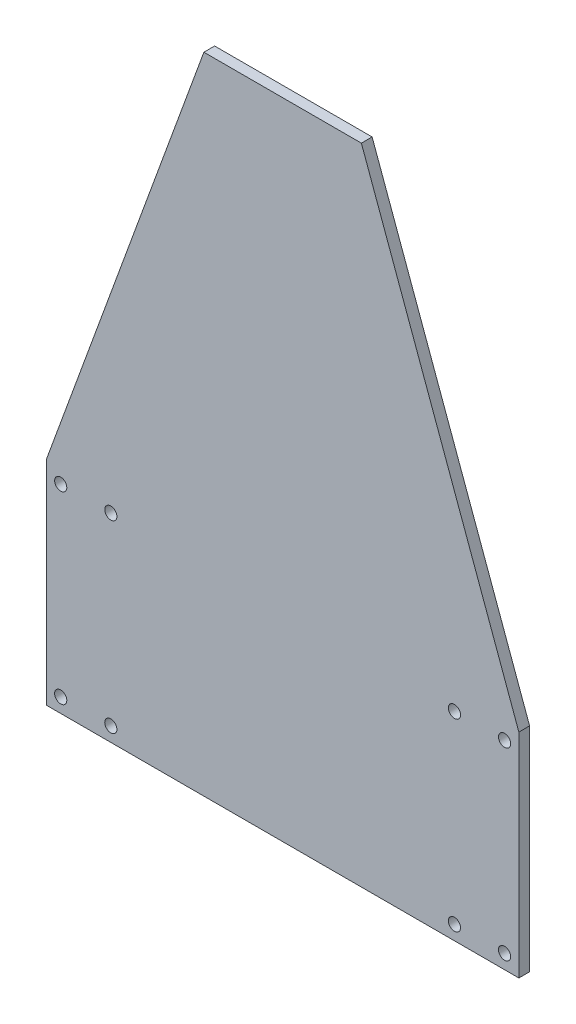
SolidWorks part; units mm, degrees
ref_plane "Front Plane" through (0, 0, 0) normal (0, 0, 1) x (1, 0, 0)
ref_plane "Top Plane" through (0, 0, 0) normal (0, 1, 0) x (1, 0, 0)
ref_plane "Right Plane" through (0, 0, 0) normal (1, 0, 0) x (0, 0, -1)
sketch "Sketch1" plane through (0, 0, 0) normal (0, 0, 1) x (1, 0, 0)
  line L0 (0, 180) -> (22, 180)
  line L1 (22, 180) -> (66, 59.5)
  line L2 (66, 59.5) -> (66, 0)
  line L3 (66, 0) -> (0, 0)
  line L4 (44, 139.899) -> (44, -55.3672) construction
  line L5 (0, 180) -> (0, 0)
  dimension "D1" = 59.5
  dimension "D2" = 180
  dimension "D3" = 22
  dimension "D4" = 66
  dimension "D5" = 22
extrude "Boss-Extrude1" add sketch "Sketch1" along normal blind 3
sketch "Sketch5" plane through (0, 0, 3) normal (0, 0, 1) x (1, 0, 0)
  line L0 (66, 0) -> (66, 59.5) construction
  line L1 (0, 0) -> (66, 0) construction
  point P0 (62, 4)
  point P1 (48, 4)
  point P2 (48, 55.5)
  point P3 (62, 55.5)
  point P4 (0, 0)
  point P5 (0, 0)
  point P6 (0, 0)
  point P7 (0, 0)
  point P8 (0, 0)
  point P9 (0, 0)
  point P10 (0, 0)
  dimension "D1" = 14
  dimension "D2" = 51.5
  dimension "D3" = 4
  dimension "D4" = 4
hole_wizard "M3 Clearance Hole1" positions "Sketch6" profile "Sketch7" hole size "M3" standard "ANSI Metric" end condition through all
sketch "Sketch6" plane through (0, 0, 3) normal (0, 0, 1) x (1, 0, 0)
  point P0 (48, 55.5)
  point P3 (62, 55.5)
  point P6 (48, 4)
  point P9 (62, 4)
sketch "Sketch7" plane through (48, 55.5, 3) normal (1, 0, 0) x (0, -1, 0)
  line L0 (0, 0) -> (0, 3)
  line L1 (0, 3) -> (1.7, 3)
  line L2 (1.7, 3) -> (1.7, 0)
  line L5 (1.7, 0) -> (0, 0)
  line L11 (0, -6.35) -> (0, 107.95) construction
  dimension "Thru Hole Dia." = 3.4
  dimension "Thru Hole Depth" = 3
mirror "Mirror1" about plane through (0, 180, 3) normal (1, 0, 0) of "M3 Clearance Hole1", "Boss-Extrude1"
